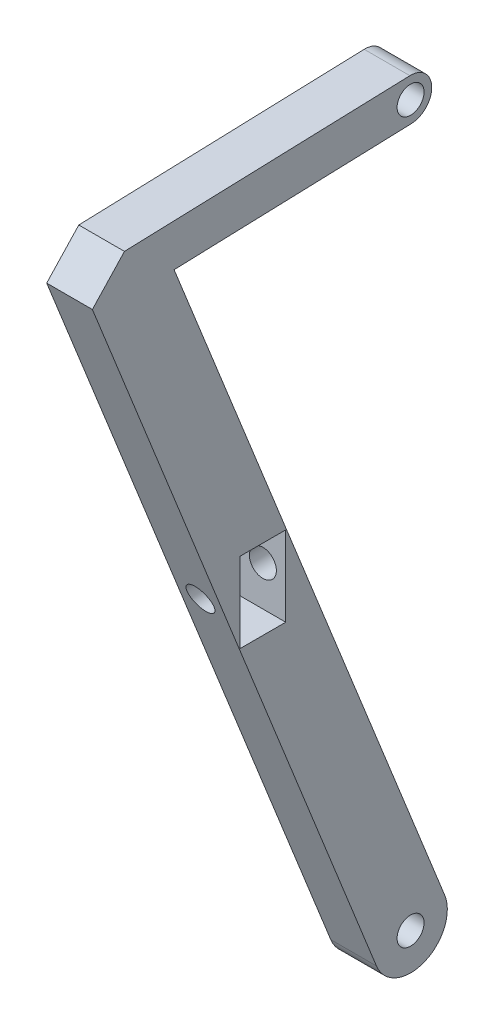
SolidWorks part; units mm, degrees
ref_plane "Front Plane" through (0, 0, 0) normal (0, 0, 1) x (1, 0, 0)
ref_plane "Top Plane" through (0, 0, 0) normal (0, 1, 0) x (1, 0, 0)
ref_plane "Right Plane" through (0, 0, 0) normal (1, 0, 0) x (0, 0, -1)
sketch "Sketch1" plane through (0, 0, 0) normal (1, 0, 0) x (0, 0, -1)
  line L3 (3.7929, 1.5163) -> (-26.2931, 76.7746)
  line L6 (-3.7929, -1.5163) -> (-35.3779, 77.4916)
  line L7 (0, 0) -> (0, 80)
  line L9 (-31.8105, 81.3009) -> (-0.0779, 82.352)
  line L13 (-0.002, 77.6575) -> (0.0779, 77.648) construction
  line L15 (-35.3779, 77.4916) -> (-31.8105, 81.3009)
  line L17 (-26.2931, 76.7746) -> (0.0779, 77.648)
  arc A0 (-0.0779, 82.352) -> (0.0779, 77.648) centre (0, 80) cw
  circle A1 centre (0, 80) radius 1.5
  arc A2 (3.7929, 1.5163) -> (-3.7929, -1.5163) centre (0, 0) cw
  circle A3 centre (0, 0) radius 1.5
  point P0 (0, 0)
  point P5 (-15.8663, 39.4745)
  point P6 (-15.8683, 79.5344)
  dimension "D1" = 3
  dimension "D2" = 3
  dimension "D3" = 80
extrude "Boss-Extrude1" add sketch "Sketch1" along normal mid plane 5.08
sketch "Sketch2" plane through (2.54, 0, 0) normal (1, 0, 0) x (0, 0, -1)
  line L4 (-16.4209, 41.076) -> (-12.628, 42.5923) construction
  line L5 (3.7929, 1.5163) -> (-26.2931, 76.7746) construction
  line L6 (-16.4209, 41.076) -> (-20.2139, 39.5597) construction
  line L7 (-3.7929, -1.5163) -> (-35.3779, 77.4916) construction
  line L9 (-13.8809, 36.631) -> (-18.9609, 36.631)
  line L10 (-13.8809, 36.631) -> (-13.8809, 45.521)
  line L11 (-13.8809, 45.521) -> (-18.9609, 45.521)
  line L12 (-18.9609, 36.631) -> (-18.9609, 45.521)
  line L13 (-13.8809, 36.631) -> (-18.9609, 45.521) construction
  line L14 (-13.8809, 45.521) -> (-18.9609, 36.631) construction
  point P6 (-16.4209, 41.076)
  dimension "D1" = 41.076
  dimension "D2" = 5.08
  dimension "D3" = 8.89
extrude "Cut-Extrude1" cut sketch "Sketch2" against normal blind 5.08
sketch "Sketch3" plane through (0, 0, 13.8809) normal (0, 0, 1) x (1, 0, 0)
  circle A0 centre (0, 41.076) radius 1.5
  dimension "D1" = 3
  dimension "D2" = 41.076
extrude "Cut-Extrude2" cut sketch "Sketch3" against normal through all both and the other way through all
